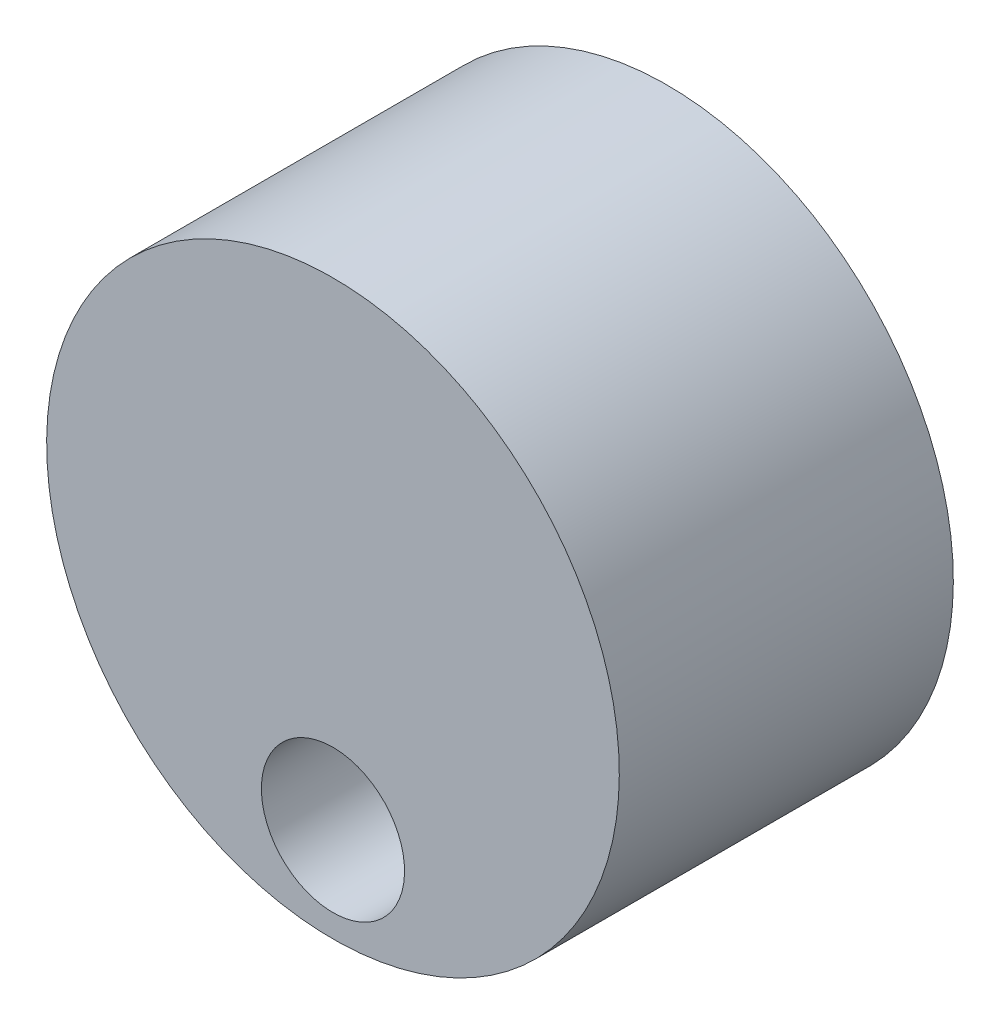
SolidWorks part; units mm, degrees
ref_plane "Plan de face" through (0, 0, 0) normal (0, 0, 1) x (1, 0, 0)
ref_plane "Plan de dessus" through (0, 0, 0) normal (0, 1, 0) x (1, 0, 0)
ref_plane "Plan de droite" through (0, 0, 0) normal (1, 0, 0) x (0, 0, -1)
sketch "Esquisse1" plane through (0, 0, 0) normal (0, 0, 1) x (1, 0, 0)
  line L0 (0, 0) -> (0, -8.509) construction
  ellipse E0 centre (0, 0) end of major axis (5.758, 11.3197) minor radius 12.7
  ellipse E1 centre (0, -8.509) end of major axis (-1.7944, -5.8897) minor radius 3.175
extrude "Boss.-Extru.1" add sketch "Esquisse1" along normal blind 14.8158
